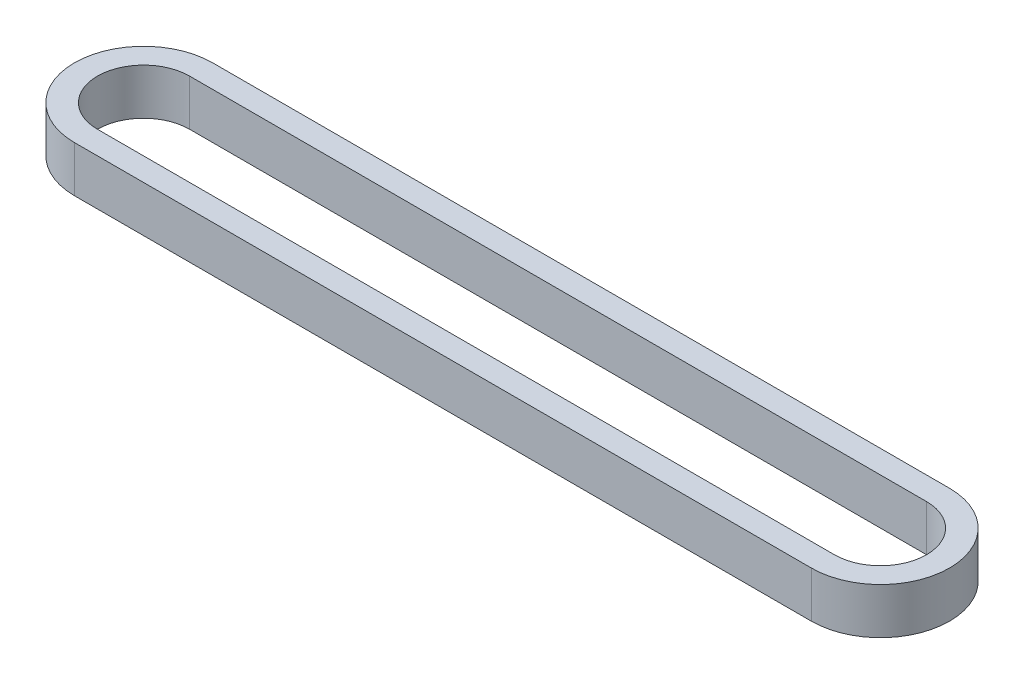
SolidWorks part; units mm, degrees
ref_plane "前视基准面" through (0, 0, 0) normal (0, 0, 1) x (1, 0, 0)
ref_plane "上视基准面" through (0, 0, 0) normal (0, 1, 0) x (1, 0, 0)
ref_plane "右视基准面" through (0, 0, 0) normal (1, 0, 0) x (0, 0, -1)
sketch "草图1" plane through (0, 0, 0) normal (0, 1, 0) x (1, 0, 0)
  line L0 (-16, 0) -> (16, 0) construction
  line L1 (-16, 2) -> (16, 2)
  line L2 (-16, -2) -> (16, -2)
  line L3 (-16, 0) -> (16, 0) construction
  line L4 (-16, 3) -> (16, 3)
  line L5 (-16, -3) -> (16, -3)
  arc A0 (-16, 2) -> (-16, -2) centre (-16, 0) ccw
  arc A1 (16, -2) -> (16, 2) centre (16, 0) ccw
  arc A2 (-16, 3) -> (-16, -3) centre (-16, 0) ccw
  arc A3 (16, -3) -> (16, 3) centre (16, 0) ccw
  point P2 (0, 0)
  point P10 (0, 0)
  dimension "D2" = 2
  dimension "D3" = 1
  dimension "D1" = 32
extrude "凸台-拉伸1" add sketch "草图1" along normal blind 2
